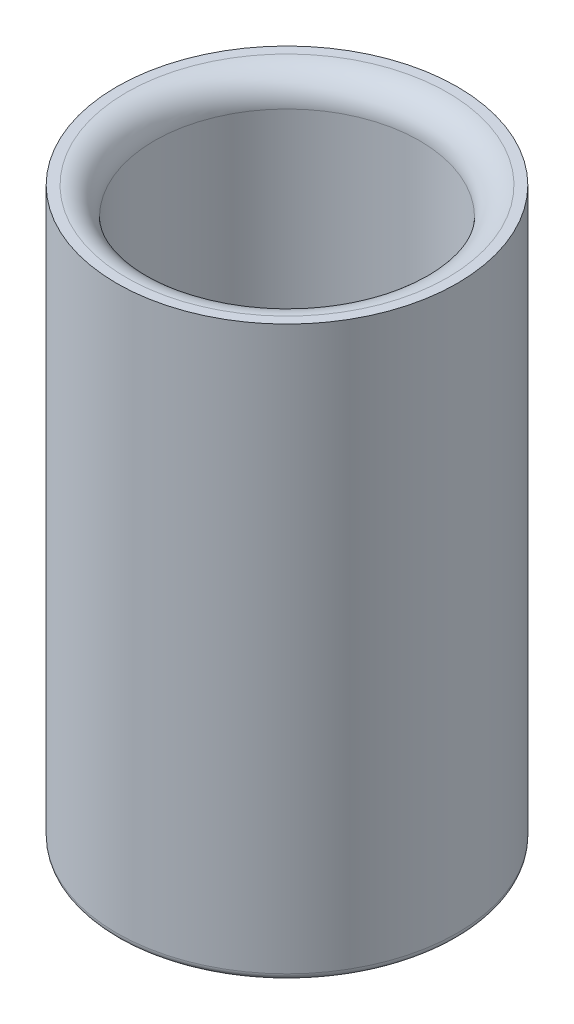
SolidWorks part; units mm, degrees
ref_plane "Płaszczyzna przednia" through (0, 0, 0) normal (0, 0, 1) x (1, 0, 0)
ref_plane "Płaszczyzna górna" through (0, 0, 0) normal (0, 1, 0) x (1, 0, 0)
ref_plane "Płaszczyzna prawa" through (0, 0, 0) normal (1, 0, 0) x (0, 0, -1)
sketch "Szkic1" plane through (0, 0, 0) normal (0, 0, 1) x (1, 0, 0)
  line L0 (0, 49.5411) -> (0, -46.2236) construction
  line L1 (0, -46.2236) -> (-11.54, -46.2236)
  line L2 (-19.02, -44.6529) -> (-19.02, 22.5164)
  line L3 (0, -46.2236) -> (0, -55.1836)
  line L4 (0, -55.1836) -> (-23.425, -55.1836)
  line L5 (-24.425, -54.1836) -> (-24.425, 26.5164)
  line L6 (-24.425, 26.5164) -> (-24.42, 26.5164)
  line L7 (-23.02, 26.5164) -> (-24.42, 26.5164)
  line L9 (-11.54, -46.2236) -> (-18.1072, -45.6491)
  arc A0 (-19.02, -44.6529) -> (-18.1072, -45.6491) centre (-18.02, -44.6529) ccw
  arc A1 (-24.425, -54.1836) -> (-23.425, -55.1836) centre (-23.425, -54.1836) ccw
  arc A2 (-19.02, 22.5164) -> (-23.02, 26.5164) centre (-23.02, 22.5164) ccw
  point P12 (-19.02, 26.5164)
  point P16 (-19.02, 26.5164)
  dimension "D1" = 1
  dimension "D7" = 11.54
  dimension "D6" = 4
  dimension "D2" = 24.425
  dimension "D3" = 19.02
  dimension "D4" = 81.7
  dimension "D5" = 8.96
  dimension "D8" = 5
revolve "Obrót1" add sketch "Szkic1" angle 360 about L0
